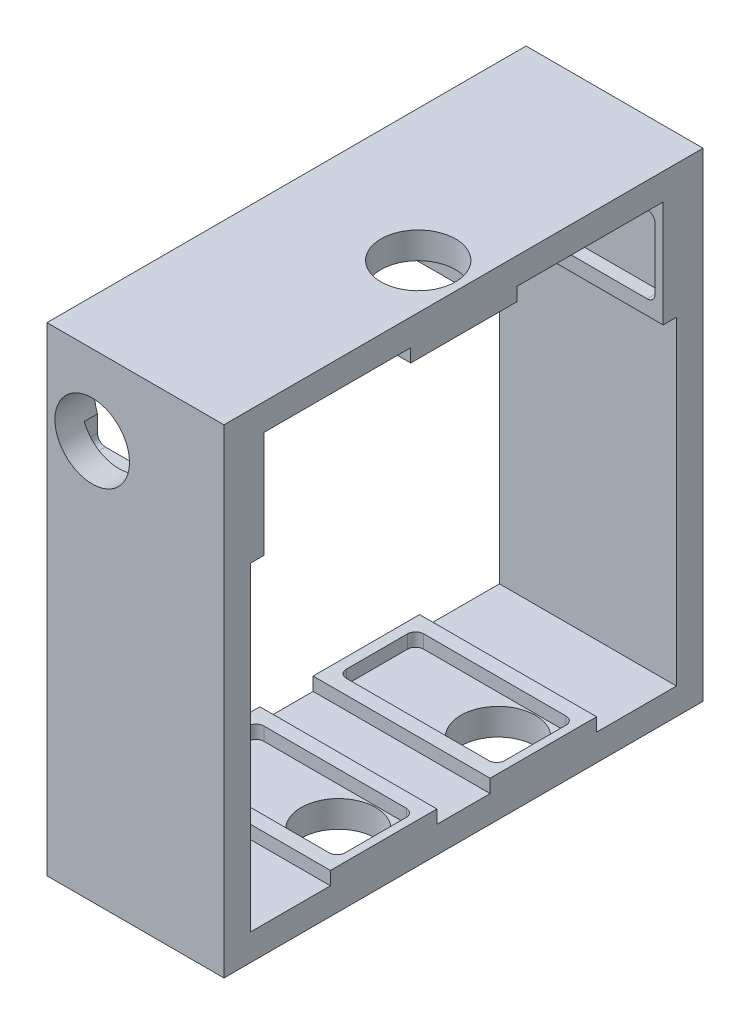
SolidWorks part; units mm, degrees
ref_plane "Front Plane" through (0, 0, 0) normal (0, 0, 1) x (1, 0, 0)
ref_plane "Top Plane" through (0, 0, 0) normal (0, 1, 0) x (1, 0, 0)
ref_plane "Right Plane" through (0, 0, 0) normal (1, 0, 0) x (0, 0, -1)
sketch "Sketch1" plane through (0, 0, 0) normal (0, 0, 1) x (1, 0, 0)
  line L1 (0, 0) -> (66.5, 0)
  line L2 (0, 0) -> (0, 180)
  line L3 (0, 180) -> (66.5, 180)
  line L4 (66.5, 0) -> (66.5, 180)
extrude "Boss-Extrude1" add sketch "Sketch1" along normal blind 180
sketch "Sketch3" plane through (0, 0, 0) normal (-1, 0, 0) x (0, 0, 1)
  line L9 (170, 10) -> (10, 10)
  line L10 (170, 10) -> (170, 170)
  line L11 (170, 170) -> (10, 170)
  line L12 (10, 10) -> (10, 170)
extrude "Cut-Extrude1" cut sketch "Sketch3" against normal blind 180
sketch "Sketch8" plane through (0, 0, 10) normal (0, 0, 1) x (1, 0, 0)
  line L0 (66.5, 170) -> (66.5, 10) construction
  line L1 (0, 170) -> (66.5, 170)
  line L2 (0, 170) -> (0, 130)
  line L3 (0, 130) -> (66.5, 130)
  line L4 (66.5, 170) -> (66.5, 130)
extrude "Boss-Extrude2" add sketch "Sketch8" along normal blind 5
sketch "Sketch10" plane through (0, 0, 170) normal (0, 0, -1) x (-1, 0, 0)
  line L0 (0, 10) -> (0, 170) construction
  line L1 (-66.5, 170) -> (0, 170)
  line L2 (-66.5, 170) -> (-66.5, 130)
  line L3 (-66.5, 130) -> (0, 130)
  line L4 (0, 170) -> (0, 130)
extrude "Boss-Extrude3" add sketch "Sketch10" along normal blind 5
sketch "Sketch5" plane through (0, 180, 0) normal (0, 1, 0) x (1, 0, 0)
  circle A1 centre (49.5, -90) radius 14
extrude "Cut-Extrude3" cut sketch "Sketch5" against normal blind 10
ref_plane "Plane4" through (0, 0, 0) normal (0, 0, -1) x (-1, 0, 0)
sketch "Sketch7" plane through (0, 0, 0) normal (0, -1, 0) x (1, 0, 0)
  circle A2 centre (49.5, 60) radius 14
  circle A3 centre (49.5, 120) radius 14
extrude "Cut-Extrude4" cut sketch "Sketch7" against normal blind 10
sketch "Sketch9" plane through (0, 0, 15) normal (0, 0, 1) x (1, 0, 0)
  line L5 (60.5, 164.5) -> (7.5, 164.5)
  line L12 (63.5, 161.5) -> (63.5, 138.5)
  line L13 (60.5, 135.5) -> (7.5, 135.5)
  line L14 (4.5, 161.5) -> (4.5, 138.5)
  arc A0 (7.5, 135.5) -> (4.5, 138.5) centre (7.5, 138.5) cw
  arc A5 (7.5, 164.5) -> (4.5, 161.5) centre (7.5, 161.5) ccw
  arc A6 (63.5, 161.5) -> (60.5, 164.5) centre (60.5, 161.5) ccw
  arc A7 (63.5, 138.5) -> (60.5, 135.5) centre (60.5, 138.5) cw
  point P3 (63.5, 150)
  dimension "D1" = 3
extrude "Cut-Extrude5" cut sketch "Sketch9" against normal blind 5
sketch "Sketch11" plane through (0, 0, 165) normal (0, 0, -1) x (-1, 0, 0)
  line L0 (-60.5, 164.5) -> (-7, 164.5)
  line L1 (-63.5, 161.5) -> (-63.5, 138.5)
  line L2 (-60.5, 135.5) -> (-7, 135.5)
  line L6 (-4, 161.5) -> (-4, 138.5)
  arc A1 (-7, 164.5) -> (-4, 161.5) centre (-7, 161.5) cw
  arc A2 (-7, 135.5) -> (-4, 138.5) centre (-7, 138.5) ccw
  arc A5 (-63.5, 138.5) -> (-60.5, 135.5) centre (-60.5, 138.5) ccw
  arc A6 (-60.5, 164.5) -> (-63.5, 161.5) centre (-60.5, 161.5) ccw
  point P8 (-57.5, 150)
  dimension "D1" = 3
  dimension "D2" = 3
extrude "Cut-Extrude6" cut sketch "Sketch11" against normal blind 5
sketch "Sketch12" plane through (0, 170, 0) normal (0, -1, 0) x (1, 0, 0)
  line L1 (66.5, 165) -> (66.5, 15) construction
  line L2 (66.5, 69.8335) -> (66.5, 109.8335)
  line L8 (66.5, 109.8335) -> (0, 109.8335)
  line L9 (66.5, 109.8335) -> (66.5, 69.8335)
  line L10 (66.5, 69.8335) -> (0, 69.8335)
  line L11 (0, 109.8335) -> (0, 69.8335)
  line L14 (60.5, 75.3335) -> (7, 75.3335)
  line L15 (63.5, 78.3335) -> (63.5, 101.3335)
  line L16 (60.5, 104.3335) -> (7, 104.3335)
  line L17 (4, 78.3335) -> (4, 101.3335)
  arc A0 (7, 104.3335) -> (4, 101.3335) centre (7, 101.3335) ccw
  arc A1 (63.5, 101.3335) -> (60.5, 104.3335) centre (60.5, 101.3335) ccw
  arc A2 (63.5, 78.3335) -> (60.5, 75.3335) centre (60.5, 78.3335) cw
  arc A3 (7, 75.3335) -> (4, 78.3335) centre (7, 78.3335) cw
  point P6 (63.5, 89.8335)
  point P7 (63.5, 89.8335)
  point P8 (57.5, 90)
  point P19 (57.5, 90)
  point P22 (66.5, 89.8335)
  dimension "D1" = 3
extrude "Boss-Extrude8" add sketch "Sketch12" along normal blind 5
sketch "Sketch13" plane through (0, 10, 0) normal (0, 1, 0) x (1, 0, 0)
  line L0 (0, -140) -> (0, -100)
  line L1 (0, -10) -> (0, -170) construction
  line L3 (66.5, -10) -> (66.5, -170) construction
  line L4 (0, -140) -> (66.5, -140)
  line L6 (0, -100) -> (66.5, -100)
  line L7 (66.5, -140) -> (66.5, -100)
  line L11 (0, -80) -> (66.5, -80)
  line L12 (0, -80) -> (0, -40)
  line L13 (0, -40) -> (66.5, -40)
  line L14 (66.5, -80) -> (66.5, -40)
  line L26 (7, -134.5) -> (60.5, -134.5)
  line L27 (4, -131.5) -> (4, -108.5)
  line L28 (7, -105.5) -> (60.5, -105.5)
  line L29 (63.5, -131.5) -> (63.5, -108.5)
  line L30 (7, -74.5) -> (60.5, -74.5)
  line L31 (4, -71.5) -> (4, -48.5)
  line L32 (7, -45.5) -> (60.5, -45.5)
  line L33 (63.5, -71.5) -> (63.5, -48.5)
  arc A0 (63.5, -71.5) -> (60.5, -74.5) centre (60.5, -71.5) cw
  arc A1 (63.5, -48.5) -> (60.5, -45.5) centre (60.5, -48.5) ccw
  arc A2 (4, -48.5) -> (7, -45.5) centre (7, -48.5) cw
  arc A3 (7, -74.5) -> (4, -71.5) centre (7, -71.5) cw
  arc A4 (63.5, -131.5) -> (60.5, -134.5) centre (60.5, -131.5) cw
  arc A5 (63.5, -108.5) -> (60.5, -105.5) centre (60.5, -108.5) ccw
  arc A6 (4, -108.5) -> (7, -105.5) centre (7, -108.5) cw
  arc A7 (7, -134.5) -> (4, -131.5) centre (7, -131.5) cw
  point P8 (0, -120)
  point P17 (0, -60)
  point P21 (63.5, -120)
  point P22 (57.5, -120)
  point P25 (63.5, -60)
  point P36 (4, -60)
  dimension "D1" = 3
extrude "Boss-Extrude9" add sketch "Sketch13" along normal blind 5
sketch "Sketch15" plane through (0, 0, 0) normal (0, 0, -1) x (-1, 0, 0)
  circle A0 centre (-17, 150) radius 14
extrude "Cut-Extrude7" cut sketch "Sketch15" against normal blind 200
